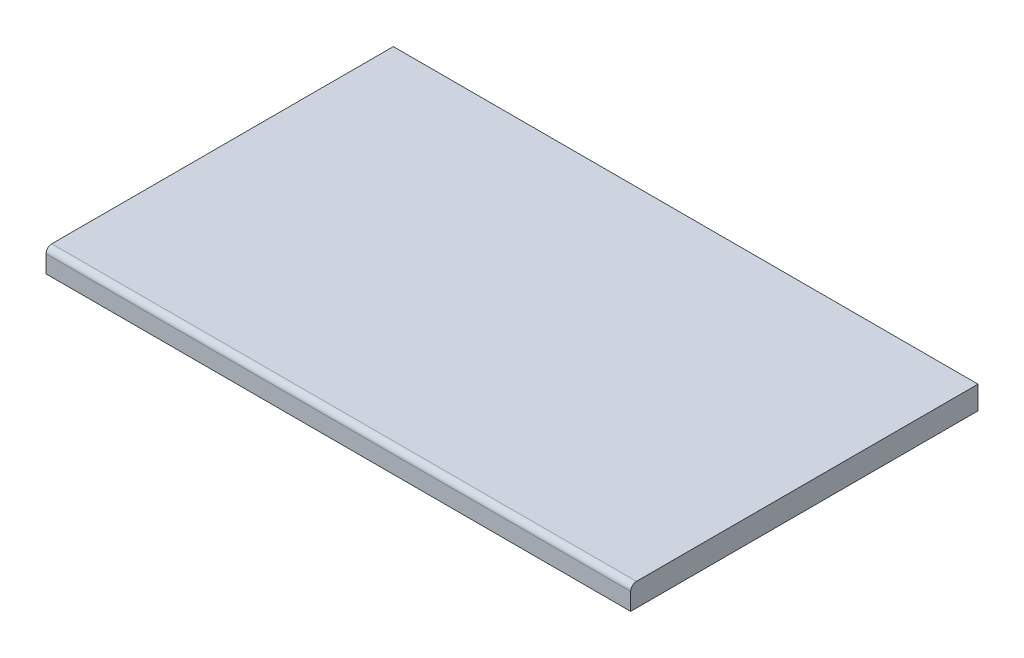
SolidWorks part; units mm, degrees
material "Maple"
ref_plane "Front Plane" through (0, 0, 0) normal (0, 0, 1) x (1, 0, 0)
ref_plane "Top Plane" through (0, 0, 0) normal (0, 1, 0) x (1, 0, 0)
ref_plane "Right Plane" through (0, 0, 0) normal (1, 0, 0) x (0, 0, -1)
sketch "Sketch1" plane through (0, 0, 0) normal (0, 1, 0) x (1, 0, 0)
  line L1 (-505, 300) -> (505, 300)
  line L2 (-505, 300) -> (-505, -300)
  line L3 (-505, -300) -> (505, -300)
  line L4 (505, 300) -> (505, -300)
  line L5 (-505, 300) -> (505, -300) construction
  line L6 (-505, -300) -> (505, 300) construction
  point P0 (0, 0)
  dimension "D1" = 1010
  dimension "D2" = 600
extrude "Boss-Extrude1" add sketch "Sketch1" along normal blind 40
fillet "Fillet1" radius 10 1 edges at (0, 40, 300)
